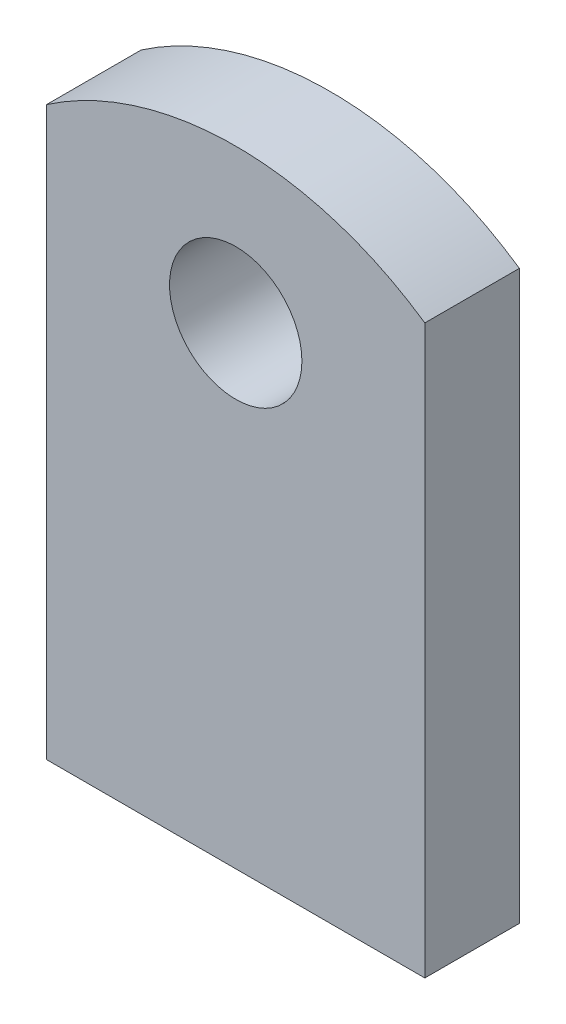
SolidWorks part; units mm, degrees
ref_plane "Front Plane" through (0, 0, 0) normal (0, 0, 1) x (1, 0, 0)
ref_plane "Top Plane" through (0, 0, 0) normal (0, 1, 0) x (1, 0, 0)
ref_plane "Right Plane" through (0, 0, 0) normal (1, 0, 0) x (0, 0, -1)
sketch "Sketch1" plane through (0, 0, 0) normal (0, 0, 1) x (1, 0, 0)
  line L1 (10, -15) -> (-10, -15)
  line L2 (10, -15) -> (10, 15)
  line L4 (-10, -15) -> (-10, 15)
  line L5 (10, -15) -> (-10, 15) construction
  line L6 (10, 15) -> (-10, -15) construction
  arc A0 (-10, 15) -> (10, 15) centre (0, 0.4198) cw
  circle A1 centre (0, 10) radius 3.5
  point P0 (0, 0)
  dimension "D2" = 17.68
  dimension "D3" = 7
  dimension "D1" = 20
  dimension "D4" = 10
  dimension "D5" = 30
  dimension "D6" = 30
extrude "Boss-Extrude1" add sketch "Sketch1" along normal blind 5
